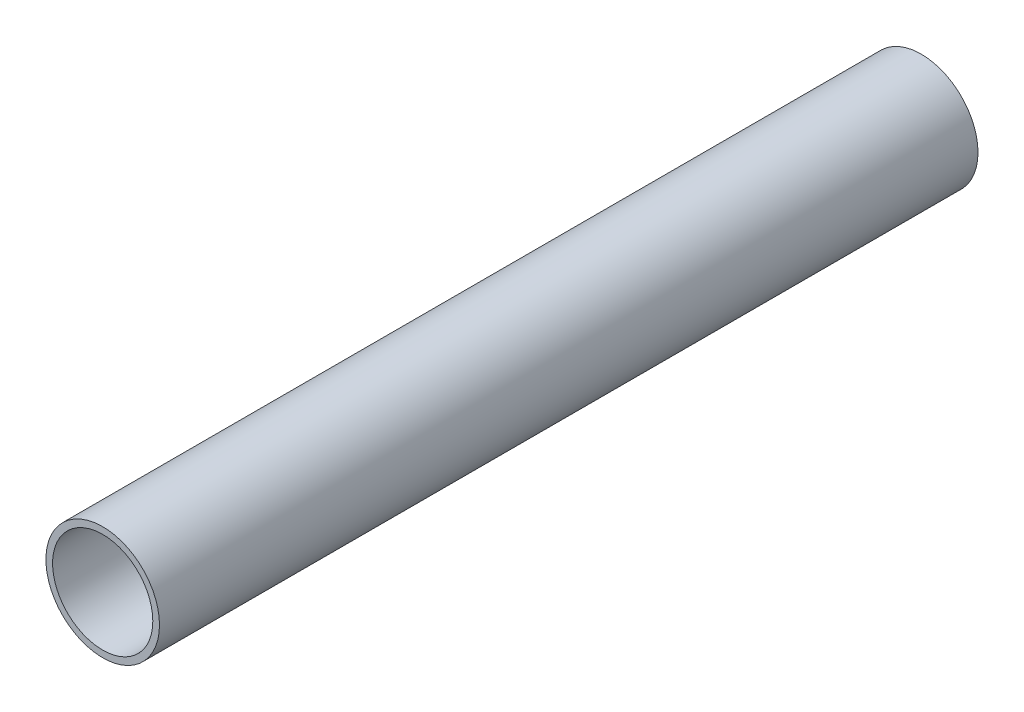
SolidWorks part; units mm, degrees
ref_plane "Front Plane" through (0, 0, 0) normal (0, 0, 1) x (1, 0, 0)
ref_plane "Top Plane" through (0, 0, 0) normal (0, 1, 0) x (1, 0, 0)
ref_plane "Right Plane" through (0, 0, 0) normal (1, 0, 0) x (0, 0, -1)
sketch "Sketch1" plane through (0, 0, 0) normal (0, 0, 1) x (1, 0, 0)
  circle A0 centre (0, 0) radius 15
  circle A1 centre (0, 0) radius 17
  dimension "D1" = 30
  dimension "D2" = 2
extrude "Boss-Extrude1" add sketch "Sketch1" along normal mid plane 245 contours A1 A0
